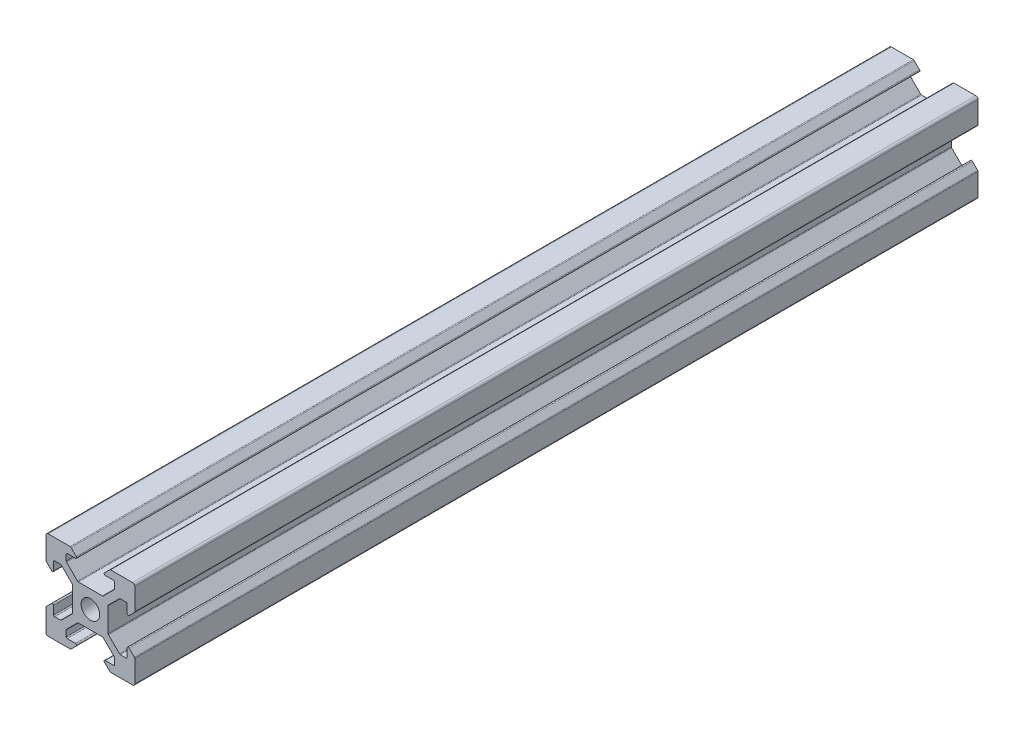
SolidWorks part; units mm, degrees
material "1060 Alloy"
ref_plane "Front Plane" through (0, 0, 0) normal (0, 0, 1) x (1, 0, 0)
ref_plane "Top Plane" through (0, 0, 0) normal (0, 1, 0) x (1, 0, 0)
ref_plane "Right Plane" through (0, 0, 0) normal (1, 0, 0) x (0, 0, -1)
sketch "Model" plane through (0, 0, 0) normal (0, 0, 1) x (1, 0, 0)
  line L0 (2012.9312, 1381.8004) -> (2012.9312, 1378.2004)
  line L1 (2016.4702, 1376.0004) -> (2017.3922, 1376.0004)
  line L2 (2020.9312, 1380.4614) -> (2020.9312, 1379.5394)
  line L3 (2016.4702, 1384.0004) -> (2017.3922, 1384.0004)
  line L270 (2012.9312, 1381.8004) -> (2012.9312, 1382.7004)
  line L271 (2012.8433, 1382.9125) -> (2010.3787, 1385.3772)
  line L272 (2010.2019, 1385.4504) -> (2008.8812, 1385.4504)
  line L273 (2008.6312, 1385.2004) -> (2008.6312, 1383.3504)
  line L274 (2008.2044, 1383.1736) -> (2007.0191, 1384.359)
  line L275 (2006.9312, 1384.5711) -> (2006.9312, 1389.5004)
  line L276 (2007.4312, 1390.0004) -> (2012.3605, 1390.0004)
  line L277 (2012.5726, 1389.9125) -> (2013.758, 1388.7272)
  line L278 (2013.5812, 1388.3004) -> (2011.7312, 1388.3004)
  line L279 (2011.4812, 1388.0504) -> (2011.4812, 1386.7297)
  line L280 (2011.5544, 1386.5529) -> (2014.0338, 1384.0736)
  line L281 (2014.2105, 1384.0004) -> (2016.4702, 1384.0004)
  line L282 (2017.3922, 1384.0004) -> (2019.6519, 1384.0004)
  line L283 (2019.8287, 1384.0736) -> (2022.308, 1386.5529)
  line L284 (2022.3812, 1386.7297) -> (2022.3812, 1388.0504)
  line L285 (2022.1312, 1388.3004) -> (2020.2812, 1388.3004)
  line L286 (2020.1044, 1388.7272) -> (2021.2898, 1389.9125)
  line L287 (2021.5019, 1390.0004) -> (2026.4312, 1390.0004)
  line L288 (2026.9312, 1389.5004) -> (2026.9312, 1384.5711)
  line L289 (2026.8433, 1384.359) -> (2025.658, 1383.1736)
  line L290 (2025.2312, 1383.3504) -> (2025.2312, 1385.2004)
  line L291 (2024.9812, 1385.4504) -> (2023.6605, 1385.4504)
  line L292 (2023.4838, 1385.3772) -> (2021.0044, 1382.8978)
  line L293 (2020.9312, 1382.7211) -> (2020.9312, 1380.4614)
  line L294 (2020.9312, 1379.5394) -> (2020.9312, 1377.2797)
  line L295 (2021.0044, 1377.1029) -> (2023.4838, 1374.6236)
  line L296 (2023.6605, 1374.5504) -> (2024.9812, 1374.5504)
  line L297 (2025.2312, 1374.8004) -> (2025.2312, 1376.6504)
  line L298 (2025.658, 1376.8272) -> (2026.8433, 1375.6418)
  line L299 (2026.9312, 1375.4297) -> (2026.9312, 1370.5004)
  line L300 (2026.4312, 1370.0004) -> (2021.5019, 1370.0004)
  line L301 (2021.2898, 1370.0883) -> (2020.1044, 1371.2736)
  line L302 (2020.2812, 1371.7004) -> (2022.1312, 1371.7004)
  line L303 (2022.3812, 1371.9504) -> (2022.3812, 1373.2711)
  line L304 (2022.308, 1373.4478) -> (2019.8287, 1375.9272)
  line L305 (2019.6519, 1376.0004) -> (2017.3922, 1376.0004)
  line L306 (2016.4702, 1376.0004) -> (2014.2105, 1376.0004)
  line L307 (2014.0338, 1375.9272) -> (2011.5544, 1373.4478)
  line L308 (2011.4812, 1373.2711) -> (2011.4812, 1371.9504)
  line L309 (2011.7312, 1371.7004) -> (2013.5812, 1371.7004)
  line L310 (2013.758, 1371.2736) -> (2012.5726, 1370.0883)
  line L311 (2012.3605, 1370.0004) -> (2007.4312, 1370.0004)
  line L312 (2006.9312, 1370.5004) -> (2006.9312, 1375.4297)
  line L313 (2007.0191, 1375.6418) -> (2008.2044, 1376.8272)
  line L314 (2008.6312, 1376.6504) -> (2008.6312, 1374.8004)
  line L315 (2008.8812, 1374.5504) -> (2010.2019, 1374.5504)
  line L316 (2010.3787, 1374.6236) -> (2012.8433, 1377.0883)
  line L317 (2012.9312, 1377.3004) -> (2012.9312, 1378.2004)
  circle A0 centre (2016.9312, 1380.0004) radius 2.1
  arc A427 (2012.9312, 1382.7004) -> (2012.8433, 1382.9125) centre (2012.6312, 1382.7004) ccw
  arc A428 (2010.3787, 1385.3772) -> (2010.2019, 1385.4504) centre (2010.2019, 1385.2004) ccw
  arc A429 (2008.8812, 1385.4504) -> (2008.6312, 1385.2004) centre (2008.8812, 1385.2004) ccw
  arc A430 (2008.2044, 1383.1736) -> (2008.6312, 1383.3504) centre (2008.3812, 1383.3504) ccw
  arc A431 (2006.9312, 1384.5711) -> (2007.0191, 1384.359) centre (2007.2312, 1384.5711) ccw
  arc A432 (2007.4312, 1390.0004) -> (2006.9312, 1389.5004) centre (2007.4312, 1389.5004) ccw
  arc A433 (2012.5726, 1389.9125) -> (2012.3605, 1390.0004) centre (2012.3605, 1389.7004) ccw
  arc A434 (2013.5812, 1388.3004) -> (2013.758, 1388.7272) centre (2013.5812, 1388.5504) ccw
  arc A435 (2011.7312, 1388.3004) -> (2011.4812, 1388.0504) centre (2011.7312, 1388.0504) ccw
  arc A436 (2011.4812, 1386.7297) -> (2011.5544, 1386.5529) centre (2011.7312, 1386.7297) ccw
  arc A437 (2014.0338, 1384.0736) -> (2014.2105, 1384.0004) centre (2014.2105, 1384.2504) ccw
  arc A441 (2019.6519, 1384.0004) -> (2019.8287, 1384.0736) centre (2019.6519, 1384.2504) ccw
  arc A442 (2022.308, 1386.5529) -> (2022.3812, 1386.7297) centre (2022.1312, 1386.7297) ccw
  arc A443 (2022.3812, 1388.0504) -> (2022.1312, 1388.3004) centre (2022.1312, 1388.0504) ccw
  arc A444 (2020.1044, 1388.7272) -> (2020.2812, 1388.3004) centre (2020.2812, 1388.5504) ccw
  arc A445 (2021.5019, 1390.0004) -> (2021.2898, 1389.9125) centre (2021.5019, 1389.7004) ccw
  arc A446 (2026.9312, 1389.5004) -> (2026.4312, 1390.0004) centre (2026.4312, 1389.5004) ccw
  arc A447 (2026.8433, 1384.359) -> (2026.9312, 1384.5711) centre (2026.6312, 1384.5711) ccw
  arc A448 (2025.2312, 1383.3504) -> (2025.658, 1383.1736) centre (2025.4812, 1383.3504) ccw
  arc A449 (2025.2312, 1385.2004) -> (2024.9812, 1385.4504) centre (2024.9812, 1385.2004) ccw
  arc A450 (2023.6605, 1385.4504) -> (2023.4838, 1385.3772) centre (2023.6605, 1385.2004) ccw
  arc A451 (2021.0044, 1382.8978) -> (2020.9312, 1382.7211) centre (2021.1812, 1382.7211) ccw
  arc A455 (2020.9312, 1377.2797) -> (2021.0044, 1377.1029) centre (2021.1812, 1377.2797) ccw
  arc A456 (2023.4838, 1374.6236) -> (2023.6605, 1374.5504) centre (2023.6605, 1374.8004) ccw
  arc A457 (2024.9812, 1374.5504) -> (2025.2312, 1374.8004) centre (2024.9812, 1374.8004) ccw
  arc A458 (2025.658, 1376.8272) -> (2025.2312, 1376.6504) centre (2025.4812, 1376.6504) ccw
  arc A459 (2026.9312, 1375.4297) -> (2026.8433, 1375.6418) centre (2026.6312, 1375.4297) ccw
  arc A460 (2026.4312, 1370.0004) -> (2026.9312, 1370.5004) centre (2026.4312, 1370.5004) ccw
  arc A461 (2021.2898, 1370.0883) -> (2021.5019, 1370.0004) centre (2021.5019, 1370.3004) ccw
  arc A462 (2020.2812, 1371.7004) -> (2020.1044, 1371.2736) centre (2020.2812, 1371.4504) ccw
  arc A463 (2022.1312, 1371.7004) -> (2022.3812, 1371.9504) centre (2022.1312, 1371.9504) ccw
  arc A464 (2022.3812, 1373.2711) -> (2022.308, 1373.4478) centre (2022.1312, 1373.2711) ccw
  arc A465 (2019.8287, 1375.9272) -> (2019.6519, 1376.0004) centre (2019.6519, 1375.7504) ccw
  arc A469 (2014.2105, 1376.0004) -> (2014.0338, 1375.9272) centre (2014.2105, 1375.7504) ccw
  arc A470 (2011.5544, 1373.4478) -> (2011.4812, 1373.2711) centre (2011.7312, 1373.2711) ccw
  arc A471 (2011.4812, 1371.9504) -> (2011.7312, 1371.7004) centre (2011.7312, 1371.9504) ccw
  arc A472 (2013.758, 1371.2736) -> (2013.5812, 1371.7004) centre (2013.5812, 1371.4504) ccw
  arc A473 (2012.3605, 1370.0004) -> (2012.5726, 1370.0883) centre (2012.3605, 1370.3004) ccw
  arc A474 (2006.9312, 1370.5004) -> (2007.4312, 1370.0004) centre (2007.4312, 1370.5004) ccw
  arc A475 (2007.0191, 1375.6418) -> (2006.9312, 1375.4297) centre (2007.2312, 1375.4297) ccw
  arc A476 (2008.6312, 1376.6504) -> (2008.2044, 1376.8272) centre (2008.3812, 1376.6504) ccw
  arc A477 (2008.6312, 1374.8004) -> (2008.8812, 1374.5504) centre (2008.8812, 1374.8004) ccw
  arc A478 (2010.2019, 1374.5504) -> (2010.3787, 1374.6236) centre (2010.2019, 1374.8004) ccw
  arc A479 (2012.8433, 1377.0883) -> (2012.9312, 1377.3004) centre (2012.6312, 1377.3004) ccw
extrude "Boss-Extrude1" add sketch "Model" along normal blind 190
